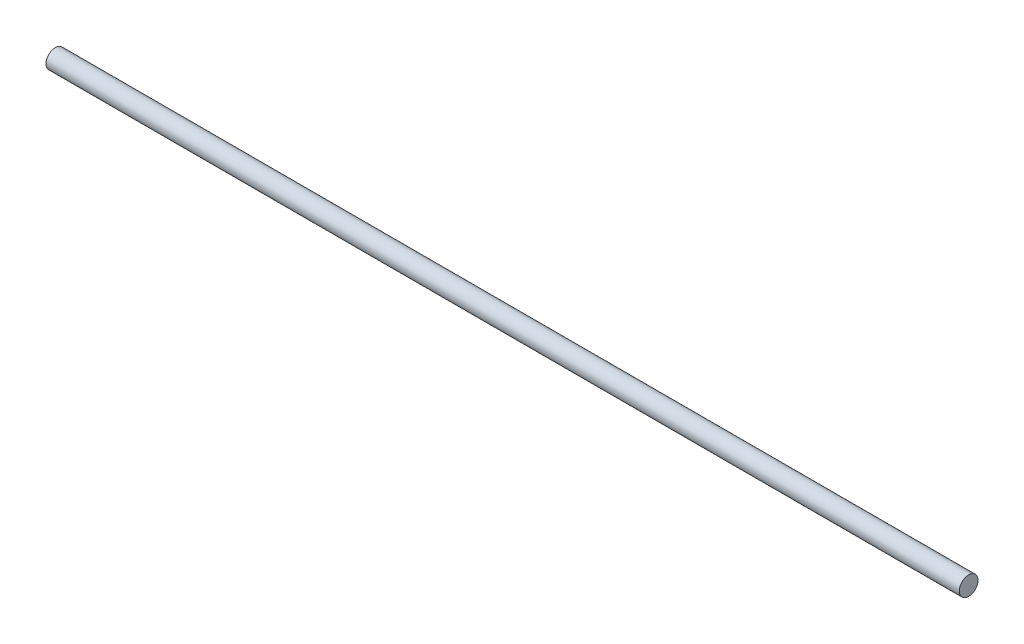
SolidWorks part; units mm, degrees
ref_plane "前视基准面" through (0, 0, 0) normal (0, 0, 1) x (1, 0, 0)
ref_plane "上视基准面" through (0, 0, 0) normal (0, 1, 0) x (1, 0, 0)
ref_plane "右视基准面" through (0, 0, 0) normal (1, 0, 0) x (0, 0, -1)
sketch "草图1" plane through (0, 0, 0) normal (1, 0, 0) x (0, 0, -1)
  circle A0 centre (0, 0) radius 4
  dimension "D1" = 8
extrude "凸台-拉伸1" add sketch "草图1" along normal blind 390
